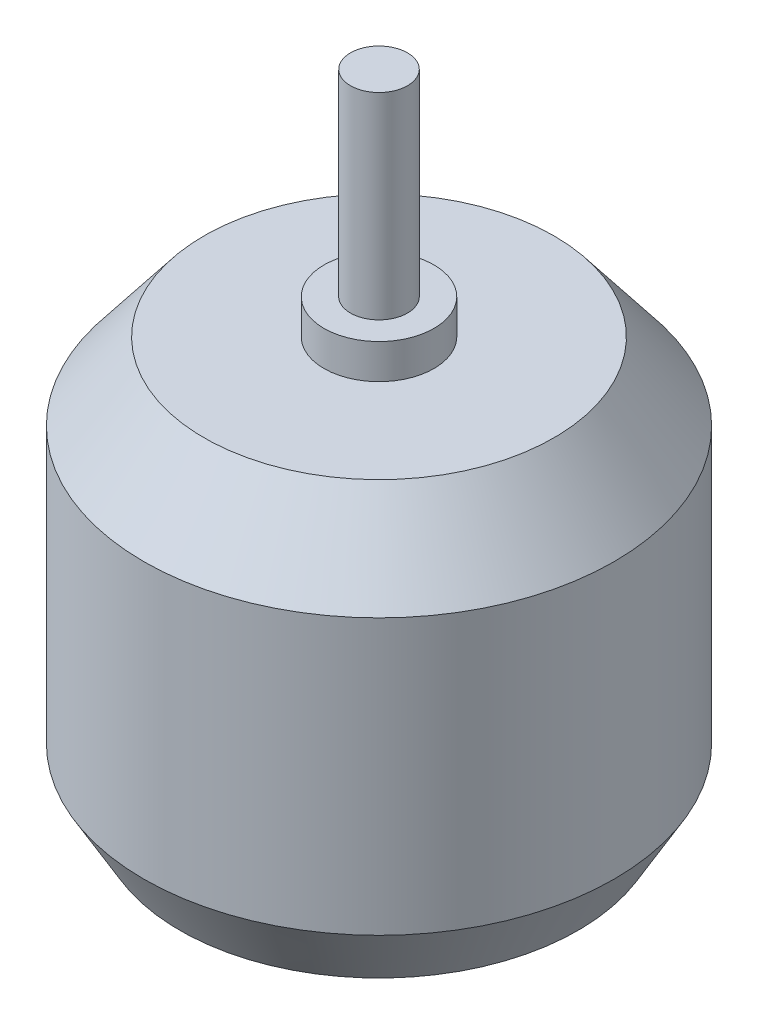
SolidWorks part; units mm, degrees
ref_plane "Front Plane" through (0, 0, 0) normal (0, 0, 1) x (1, 0, 0)
ref_plane "Top Plane" through (0, 0, 0) normal (0, 1, 0) x (1, 0, 0)
ref_plane "Right Plane" through (0, 0, 0) normal (1, 0, 0) x (0, 0, -1)
sketch "Sketch1" plane through (0, 0, 0) normal (0, 0, 1) x (1, 0, 0)
  line L0 (0, 0) -> (0, 43.64)
  line L1 (0, 43.64) -> (18.4187, 43.64)
  line L2 (18.4187, 43.64) -> (24.76, 35.5235)
  line L3 (24.76, 35.5235) -> (24.76, 6.5818)
  line L4 (24.76, 6.5818) -> (20.96, 0)
  line L5 (20.96, 0) -> (0, 0)
  line L6 (0, 0) -> (0, 59.568) construction
  dimension "D1" = 24.76
  dimension "D2" = 43.64
  dimension "D3" = 142
  dimension "D4" = 150
  dimension "D5" = 10.3
  dimension "D6" = 7.6
revolve "Revolve1" add sketch "Sketch1" angle 360 about L6
sketch "Sketch2" plane through (0, 43.64, 0) normal (0, 1, 0) x (1, 0, 0)
  circle A0 centre (0, 0) radius 3
  dimension "D1" = 6
extrude "Boss-Extrude1" add sketch "Sketch2" along normal blind 24.39
sketch "Sketch4" plane through (0, 43.64, 0) normal (0, 1, 0) x (1, 0, 0)
  circle A0 centre (0, 0) radius 5.79
extrude "Boss-Extrude2" add sketch "Sketch4" along normal blind 3.66
